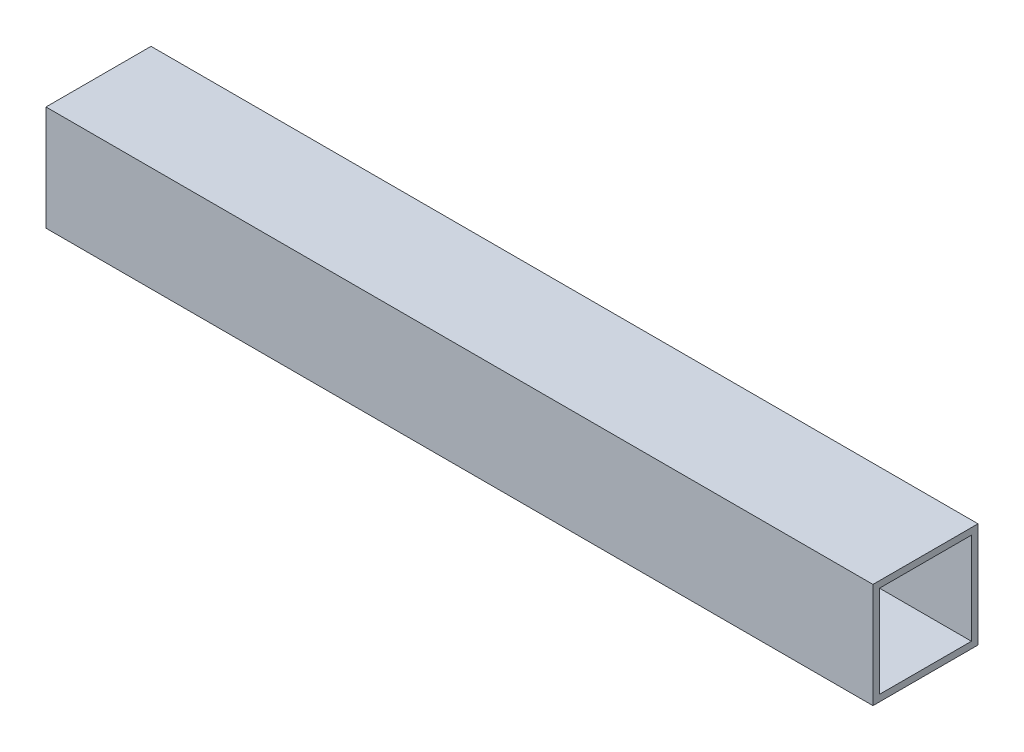
SolidWorks part; units mm, degrees
ref_plane "Front Plane" through (0, 0, 0) normal (0, 0, 1) x (1, 0, 0)
ref_plane "Top Plane" through (0, 0, 0) normal (0, 1, 0) x (1, 0, 0)
ref_plane "Right Plane" through (0, 0, 0) normal (1, 0, 0) x (0, 0, -1)
sketch "Sketch2" plane through (0, 0, 0) normal (1, 0, 0) x (0, 0, -1)
  line L1 (12.7, -12.7) -> (-12.7, -12.7)
  line L2 (12.7, -12.7) -> (12.7, 12.7)
  line L3 (12.7, 12.7) -> (-12.7, 12.7)
  line L4 (-12.7, -12.7) -> (-12.7, 12.7)
  line L5 (12.7, -12.7) -> (-12.7, 12.7) construction
  line L6 (12.7, 12.7) -> (-12.7, -12.7) construction
  line L7 (11.1125, -11.1125) -> (-11.1125, -11.1125)
  line L8 (11.1125, -11.1125) -> (11.1125, 11.1125)
  line L9 (11.1125, 11.1125) -> (-11.1125, 11.1125)
  line L10 (-11.1125, -11.1125) -> (-11.1125, 11.1125)
  line L11 (11.1125, -11.1125) -> (-11.1125, 11.1125) construction
  line L12 (11.1125, 11.1125) -> (-11.1125, -11.1125) construction
  point P0 (0, 0)
  point P6 (0, 0)
  dimension "D1" = 25.4
  dimension "D2" = 25.4
  dimension "D3" = 1.5875
  dimension "D4" = 1.5875
extrude "Boss-Extrude2" add sketch "Sketch2" along normal blind 200
